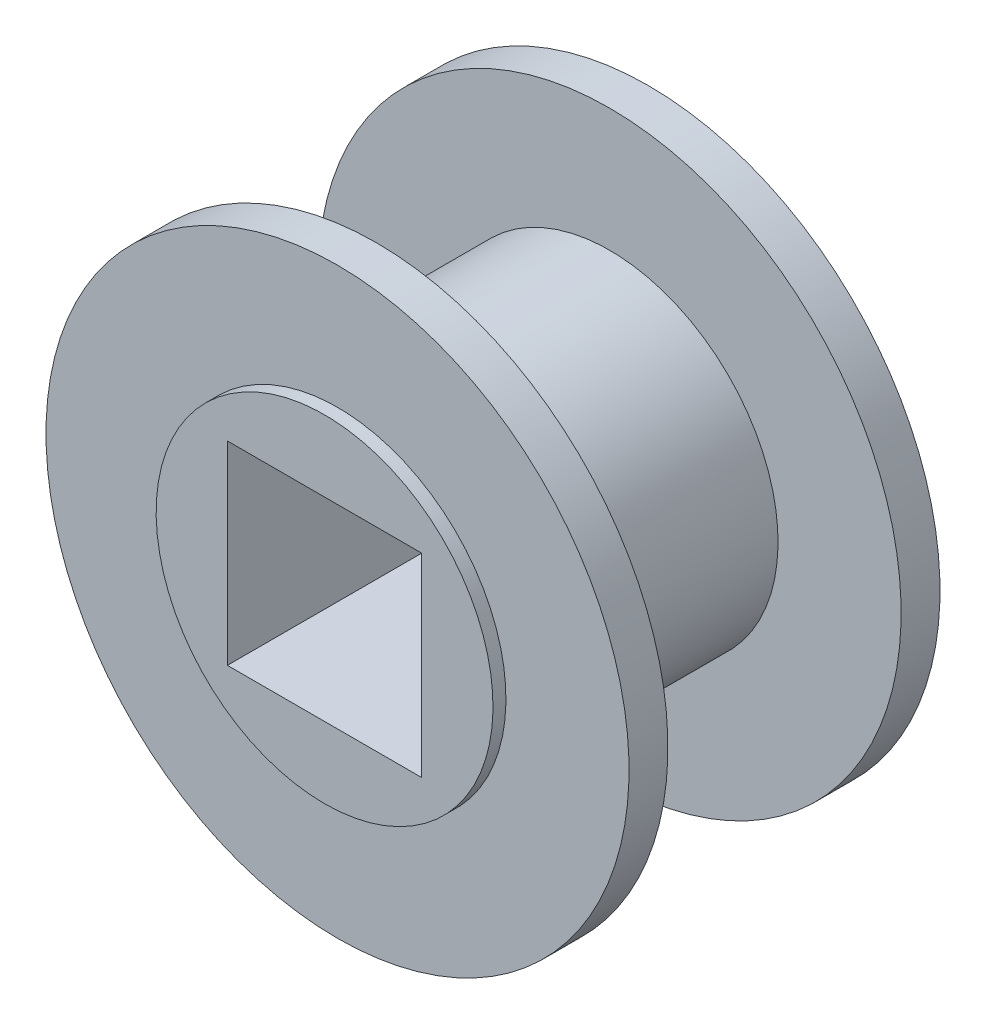
SolidWorks part; units mm, degrees
ref_plane "Piano frontale" through (0, 0, 0) normal (0, 0, 1) x (1, 0, 0)
ref_plane "Piano superiore" through (0, 0, 0) normal (0, 1, 0) x (1, 0, 0)
ref_plane "Piano destro" through (0, 0, 0) normal (1, 0, 0) x (0, 0, -1)
sketch "Schizzo1" plane through (0, 0, 0) normal (1, 0, 0) x (0, 0, -1)
  line L0 (-19.5818, 0) -> (19.5818, 0) construction
  line L1 (-13, 0) -> (-13, 13)
  line L2 (-13, 13) -> (-12, 13)
  line L3 (-12, 13) -> (-12, 22.5)
  line L4 (-12, 22.5) -> (-9, 22.5)
  line L5 (-9, 22.5) -> (-9, 13)
  line L6 (-9, 13) -> (9, 13)
  line L7 (9, 13) -> (9, 22.5)
  line L8 (9, 22.5) -> (12, 22.5)
  line L9 (12, 22.5) -> (12, 13)
  line L10 (12, 13) -> (13, 13)
  line L11 (13, 13) -> (13, 0)
  line L12 (-13, 0) -> (13, 0)
  point P3 (0, 13)
  point P4 (0, 0)
  dimension "D1" = 13
  dimension "D2" = 22.5
  dimension "D3" = 3
  dimension "D4" = 3
  dimension "D5" = 26
  dimension "D6" = 18
revolve "Rivoluzione1" add sketch "Schizzo1" angle 360 about L0
sketch "Schizzo2" plane through (0, 0, 13) normal (0, 0, 1) x (1, 0, 0)
  line L1 (-7.5, -7.5) -> (7.5, -7.5)
  line L2 (-7.5, -7.5) -> (-7.5, 7.5)
  line L3 (-7.5, 7.5) -> (7.5, 7.5)
  line L4 (7.5, -7.5) -> (7.5, 7.5)
  line L5 (-7.5, -7.5) -> (7.5, 7.5) construction
  line L6 (-7.5, 7.5) -> (7.5, -7.5) construction
  point P0 (0, 0)
  dimension "D1" = 15
extrude "Taglio-Estrusione1" cut sketch "Schizzo2" against normal through all
sketch "Schizzo3" plane through (0, 0, 0) normal (1, 0, 0) x (0, 0, -1)
  line L0 (13, -13) -> (13, 13) construction
  circle A0 centre (7, 0) radius 1.5
  point P4 (0, 0)
  dimension "D1" = 3
  dimension "D2" = 6
extrude "Taglio-Estrusione2" cut sketch "Schizzo3" against normal up to next
